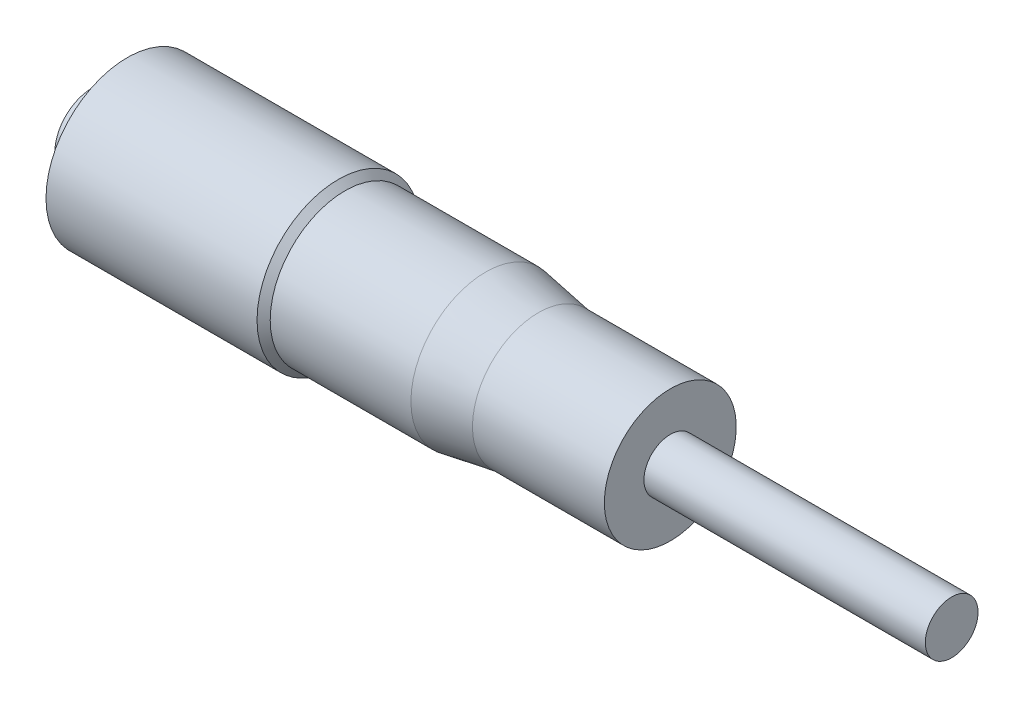
SolidWorks part; units mm, degrees
ref_plane "Front Plane" through (0, 0, 0) normal (0, 0, 1) x (1, 0, 0)
ref_plane "Top Plane" through (0, 0, 0) normal (0, 1, 0) x (1, 0, 0)
ref_plane "Right Plane" through (0, 0, 0) normal (1, 0, 0) x (0, 0, -1)
sketch "Sketch1" plane through (0, 0, 0) normal (0, 0, 1) x (1, 0, 0)
  line L0 (0, 0) -> (88.5234, 0) construction
  line L1 (-49.375, 0) -> (49.375, 0)
  line L2 (49.375, 0) -> (49.375, 3)
  line L3 (49.375, 3) -> (17.375, 3)
  line L4 (17.375, 3) -> (17.375, 7.5)
  line L5 (17.375, 7.5) -> (2.375, 7.5)
  line L6 (2.375, 7.5) -> (-3.625, 8.5)
  line L7 (-3.625, 8.5) -> (-19.625, 8.5)
  line L8 (-19.625, 8.5) -> (-20.375, 9.25)
  line L9 (-20.375, 9.25) -> (-44.375, 9.25)
  line L10 (-44.375, 9.25) -> (-45.875, 4.25)
  line L11 (-45.875, 4.25) -> (-48.375, 4.25)
  arc A0 (-48.375, 4.25) -> (-49.375, 0) centre (-39.8437, 0) ccw
  point P5 (0, 0)
  point P16 (-31.476, 0)
  point P17 (0, 0)
  point P18 (0, 0)
  dimension "D1" = 32
  dimension "D2" = 3
  dimension "D3" = 7.5
  dimension "D4" = 15
  dimension "D5" = 8.5
  dimension "D6" = 6
  dimension "D7" = 9.25
  dimension "D8" = 135
  dimension "D9" = 16
  dimension "D10" = 24
  dimension "D11" = 1.5
  dimension "D12" = 5
  dimension "D13" = 2.5
  dimension "D14" = 1
revolve "Revolve1" add sketch "Sketch1" angle 360 about L0
